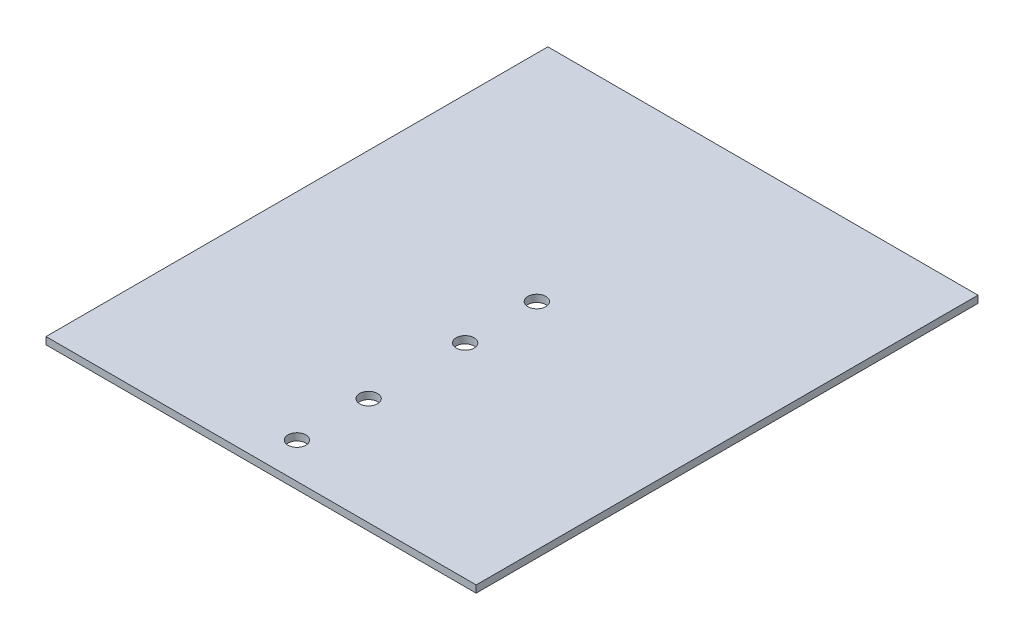
SolidWorks part; units mm, degrees
ref_plane "Front Plane" through (0, 0, 0) normal (0, 0, 1) x (1, 0, 0)
ref_plane "Top Plane" through (0, 0, 0) normal (0, 1, 0) x (1, 0, 0)
ref_plane "Right Plane" through (0, 0, 0) normal (1, 0, 0) x (0, 0, -1)
sketch "Sketch1" plane through (0, 0, 0) normal (0, 1, 0) x (1, 0, 0)
  line L1 (-76.2, -88.9) -> (76.2, -88.9)
  line L2 (-76.2, -88.9) -> (-76.2, 88.9)
  line L3 (-76.2, 88.9) -> (76.2, 88.9)
  line L4 (76.2, -88.9) -> (76.2, 88.9)
  line L5 (-76.2, -88.9) -> (76.2, 88.9) construction
  line L6 (-76.2, 88.9) -> (76.2, -88.9) construction
  point P0 (0, 0)
  dimension "D1" = 152.4
  dimension "D2" = 177.8
extrude "Boss-Extrude1" add sketch "Sketch1" along normal blind 2.54
hole_wizard "1/4 (0.25) Diameter Hole1" positions "Sketch3" profile "Sketch2" hole size "1/4" standard "ANSI Inch" end condition up to next
sketch "Sketch3" plane through (0, 0, 0) normal (0, -1, 0) x (-1, 0, 0)
  point P0 (0, -76.2)
  point P3 (0, -50.8)
  point P6 (0, 8.7992)
  point P9 (0, -16.6008)
sketch "Sketch2" plane through (0, 0, 76.2) normal (1, 0, 0) x (0, 0, -1)
  line L0 (0, 0) -> (0, 2.54)
  line L1 (0, 2.54) -> (3.175, 2.54)
  line L2 (3.175, 2.54) -> (3.175, 0)
  line L5 (3.175, 0) -> (0, 0)
  line L11 (0, -6.35) -> (0, 107.95) construction
  dimension "Thru Hole Dia." = 6.35
  dimension "Thru Hole Depth" = 2.54
